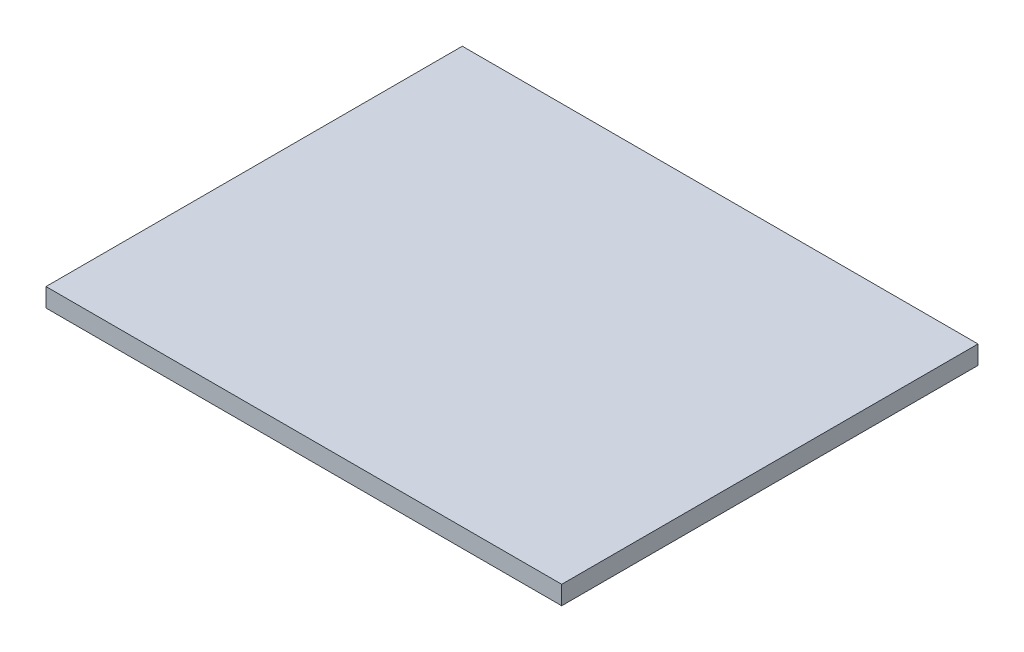
SolidWorks part; units mm, degrees
ref_plane "Front Plane" through (0, 0, 0) normal (0, 0, 1) x (1, 0, 0)
ref_plane "Top Plane" through (0, 0, 0) normal (0, 1, 0) x (1, 0, 0)
ref_plane "Right Plane" through (0, 0, 0) normal (1, 0, 0) x (0, 0, -1)
sketch "Sketch1" plane through (0, 0, 0) normal (0, 1, 0) x (1, 0, 0)
  line L0 (0, 33.5) -> (83, 33.5) construction
  line L1 (0, 0) -> (83, 0)
  line L2 (0, 0) -> (0, 67)
  line L3 (0, 67) -> (83, 67)
  line L4 (83, 0) -> (83, 67)
  line L5 (41.5, 67) -> (41.5, 0) construction
  dimension "D1" = 83
  dimension "D2" = 67
extrude "Boss-Extrude1" add sketch "Sketch1" along normal blind 3
